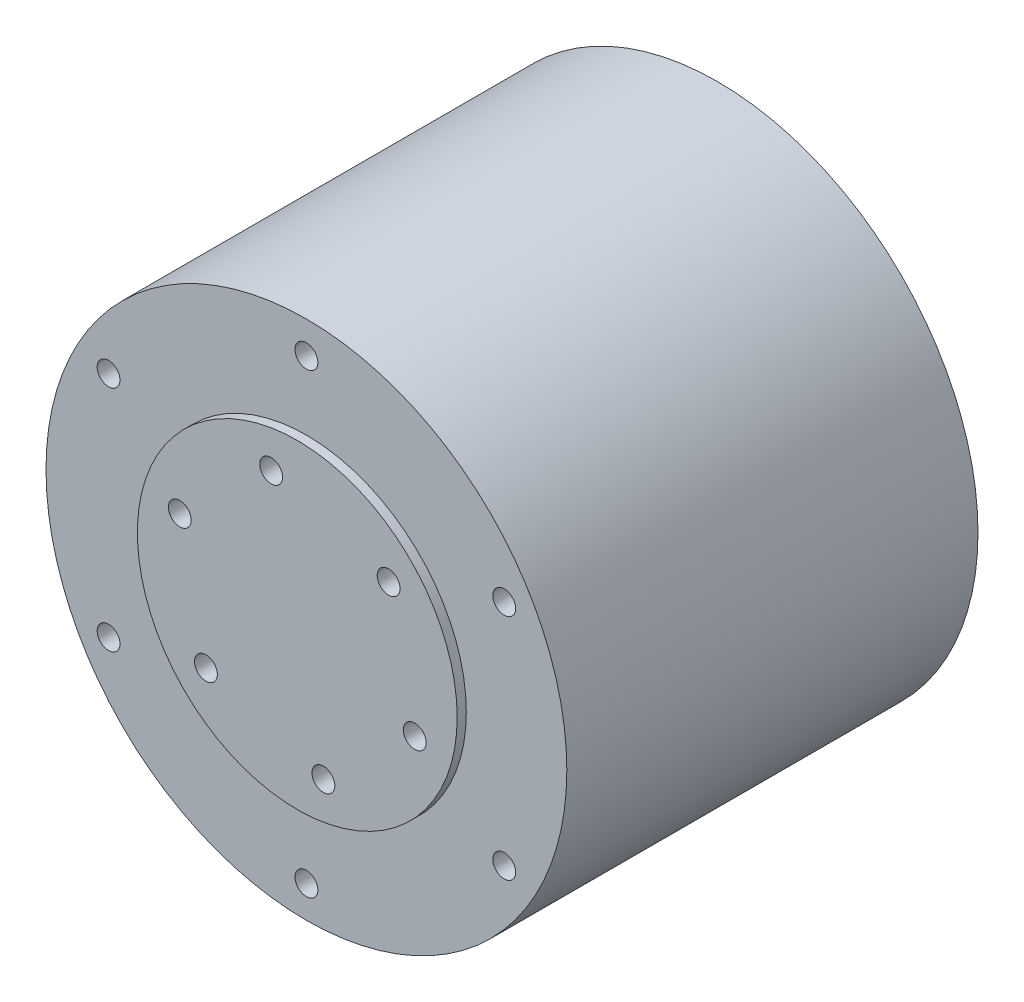
SolidWorks part; units mm, degrees
ref_plane "前视基准面" through (0, 0, 0) normal (0, 0, 1) x (1, 0, 0)
ref_plane "上视基准面" through (0, 0, 0) normal (0, 1, 0) x (1, 0, 0)
ref_plane "右视基准面" through (0, 0, 0) normal (1, 0, 0) x (0, 0, -1)
other "Configuration Table"
sketch "草图1" plane through (0, 0, 0) normal (0, 0, 1) x (1, 0, 0)
  circle A0 centre (0, 0) radius 28.5
  dimension "D1" = 57
extrude "凸台-拉伸1" add sketch "草图1" along normal blind 45
sketch "草图2" plane through (0, 0, 45) normal (0, 0, 1) x (1, 0, 0)
  circle A0 centre (0, 0) radius 17.5
  dimension "D1" = 35
extrude "凸台-拉伸2" add sketch "草图2" along normal blind 1
sketch "草图3" plane through (0, 0, 45) normal (0, 0, 1) x (1, 0, 0)
  circle A0 centre (0, 0) radius 25 construction
  circle A1 centre (0, 25) radius 1.5
  circle A2 centre (21.6506, 12.5) radius 1.5
  circle A3 centre (21.6506, -12.5) radius 1.5
  circle A4 centre (0, -25) radius 1.5
  circle A5 centre (-21.6506, -12.5) radius 1.5
  circle A6 centre (-21.6506, 12.5) radius 1.5
  point P18 (0, 0)
  dimension "D1" = 50
  dimension "D2" = 3
  dimension "D3" = 6
hole_wizard "M3x0.5 螺纹孔1" positions "3D草图1" profile "草图4" tap size "M3x0.5" standard "ANSI Metric"
sketch3d "3D草图1"
  point P0 (0, 25, 45)
  point P3 (21.6506, 12.5, 45)
  point P6 (21.6506, -12.5, 45)
  point P9 (0, -25, 45)
  point P12 (-21.6506, -12.5, 45)
  point P15 (-21.6506, 12.5, 45)
sketch "草图4" plane through (0, 25, 45) normal (1, 0, 0) x (0, -1, 0)
  line L0 (0, 0) -> (0, 5)
  line L1 (0, 5) -> (1.25, 4.2489)
  line L2 (1.25, 4.2489) -> (1.25, 0)
  line L5 (1.25, 0) -> (0, 0)
  line L10 (0, 5) -> (-1.25, 4.2489) construction
  line L11 (0, -6.35) -> (0, 107.95) construction
  dimension "螺纹孔钻头直径" = 2.5
  dimension "螺纹孔钻头深度" = 5
  dimension "导头角度" = 118
cosmetic thread "孔螺蚊线1" parameters "D1"=6, "D2"=3
cosmetic thread "孔螺蚊线2" parameters "D1"=6, "D2"=3
cosmetic thread "孔螺蚊线3" parameters "D1"=6, "D2"=3
cosmetic thread "孔螺蚊线4" parameters "D1"=6, "D2"=3
cosmetic thread "孔螺蚊线5" parameters "D1"=6, "D2"=3
cosmetic thread "孔螺蚊线6" parameters "D1"=6, "D2"=3
sketch "草图5" plane through (0, 0, 46) normal (0, 0, 1) x (1, 0, 0)
  circle A0 centre (0, 0) radius 13.5 construction
  circle A1 centre (9.9976, 9.0719) radius 1.5
  circle A2 centre (12.8552, -4.1222) radius 1.5
  circle A3 centre (2.8577, -13.1941) radius 1.5
  circle A4 centre (-9.9976, -9.0719) radius 1.5
  circle A5 centre (-12.8552, 4.1222) radius 1.5
  circle A6 centre (-2.8577, 13.1941) radius 1.5
  point P18 (0, 0)
  dimension "D1" = 27
  dimension "D3" = 3
  dimension "D2" = 6
hole_wizard "M3x0.5 螺纹孔2" positions "3D草图2" profile "草图6" tap size "M3x0.5" standard "ANSI Metric"
sketch3d "3D草图2"
  point P0 (-2.8577, 13.1941, 46)
  point P3 (9.9976, 9.0719, 46)
  point P6 (12.8552, -4.1222, 46)
  point P9 (2.8577, -13.1941, 46)
  point P12 (-9.9976, -9.0719, 46)
  point P17 (-12.8552, 4.1222, 46)
sketch "草图6" plane through (-2.8577, 13.1941, 46) normal (1, 0, 0) x (0, -1, 0)
  line L0 (0, 0) -> (0, 5)
  line L1 (0, 5) -> (1.25, 4.2489)
  line L2 (1.25, 4.2489) -> (1.25, 0)
  line L5 (1.25, 0) -> (0, 0)
  line L10 (0, 5) -> (-1.25, 4.2489) construction
  line L11 (0, -6.35) -> (0, 107.95) construction
  dimension "螺纹孔钻头直径" = 2.5
  dimension "螺纹孔钻头深度" = 5
  dimension "导头角度" = 118
cosmetic thread "孔螺蚊线7" parameters "D1"=6, "D2"=3
cosmetic thread "孔螺蚊线8" parameters "D1"=6, "D2"=3
cosmetic thread "孔螺蚊线9" parameters "D1"=6, "D2"=3
cosmetic thread "孔螺蚊线10" parameters "D1"=6, "D2"=3
cosmetic thread "孔螺蚊线11" parameters "D1"=6, "D2"=3
cosmetic thread "孔螺蚊线12" parameters "D1"=6, "D2"=3
sketch "草图7" plane through (0, 0, 0) normal (0, 0, -1) x (-1, 0, 0)
  circle A0 centre (0, 0) radius 19 construction
  circle A1 centre (13.435, 13.435) radius 1.5
  circle A2 centre (13.435, -13.435) radius 1.5
  circle A3 centre (-13.435, -13.435) radius 1.5
  circle A4 centre (-13.435, 13.435) radius 1.5
  point P14 (0, 0)
  dimension "D1" = 38
  dimension "D3" = 3
  dimension "D2" = 4
hole_wizard "M3x0.5 螺纹孔3" positions "3D草图3" profile "草图8" tap size "M3x0.5" standard "ANSI Metric"
sketch3d "3D草图3"
  point P0 (13.435, 13.435, 0)
  point P3 (13.435, -13.435, 0)
  point P6 (-13.435, -13.435, 0)
  point P9 (-13.435, 13.435, 0)
sketch "草图8" plane through (13.435, 13.435, 0) normal (1, 0, 0) x (0, 1, 0)
  line L0 (0, 0) -> (0, 5)
  line L1 (0, 5) -> (1.25, 4.2489)
  line L2 (1.25, 4.2489) -> (1.25, 0)
  line L5 (1.25, 0) -> (0, 0)
  line L10 (0, 5) -> (-1.25, 4.2489) construction
  line L11 (0, -6.35) -> (0, 107.95) construction
  dimension "螺纹孔钻头直径" = 2.5
  dimension "螺纹孔钻头深度" = 5
  dimension "导头角度" = 118
cosmetic thread "孔螺蚊线13" parameters "D1"=6, "D2"=3
cosmetic thread "孔螺蚊线14" parameters "D1"=6, "D2"=3
cosmetic thread "孔螺蚊线15" parameters "D1"=6, "D2"=3
cosmetic thread "孔螺蚊线16" parameters "D1"=6, "D2"=3
